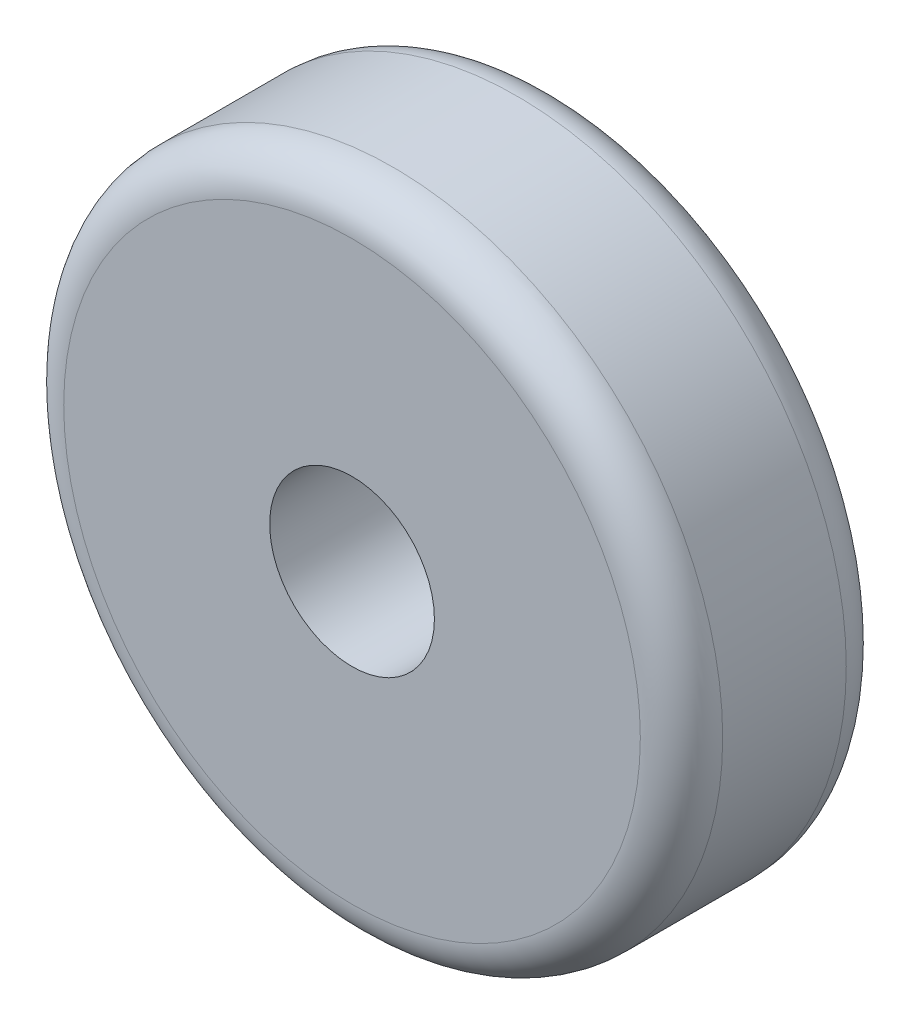
SolidWorks part; units mm, degrees
ref_plane "前视基准面" through (0, 0, 0) normal (0, 0, 1) x (1, 0, 0)
ref_plane "上视基准面" through (0, 0, 0) normal (0, 1, 0) x (1, 0, 0)
ref_plane "右视基准面" through (0, 0, 0) normal (1, 0, 0) x (0, 0, -1)
other "Configuration Table"
sketch "草图1" plane through (0, 0, 0) normal (0, 0, 1) x (1, 0, 0)
  circle A0 centre (0, 0) radius 8
  circle A1 centre (0, 0) radius 2
  dimension "D1" = 4
  dimension "D2" = 16
extrude "凸台-拉伸1" add sketch "草图1" along normal blind 5
fillet "圆角1" radius 1 2 edges at (8, 0, 0) (8, 0, 5)
